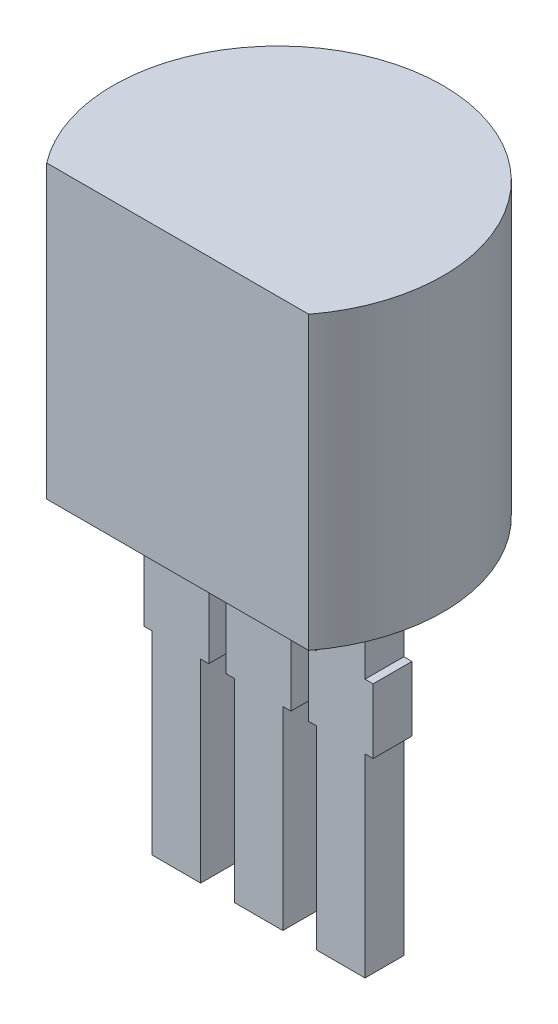
SolidWorks part; units mm, degrees
ref_plane "Спереди" through (0, 0, 0) normal (0, 0, 1) x (1, 0, 0)
ref_plane "Сверху" through (0, 0, 0) normal (0, 1, 0) x (1, 0, 0)
ref_plane "Справа" through (0, 0, 0) normal (1, 0, 0) x (0, 0, -1)
sketch "Эскиз1" plane through (0, 0, 0) normal (0, 1, 0) x (1, 0, 0)
  line L0 (-2.0248, -1.55) -> (2.0248, -1.55)
  arc A0 (2.0248, -1.55) -> (-2.0248, -1.55) centre (0, 0) ccw
  point P5 (0, 0)
  point P6 (2.0248, -1.55)
  point P7 (-2.0248, -1.55)
  dimension "D1" = 5.1
  dimension "D2" = 1.55
extrude "Бобышка-Вытянуть1" add sketch "Эскиз1" along normal blind 4.5
sketch "Эскиз3" plane through (0, 0, 0) normal (0, 0, 1) x (1, 0, 0)
  line L0 (0, 2.0104) -> (0, -3.7717) construction
  line L1 (-1.27, -4.7725) -> (-1.27, 1.9377) construction
  line L2 (1.27, -4.7725) -> (1.27, 1.8672) construction
  line L3 (-1.645, 0) -> (-1.645, -1.2)
  line L4 (-1.645, -1.2) -> (-1.77, -1.2)
  line L5 (-1.77, -1.2) -> (-1.77, -2.2)
  line L6 (-1.77, -2.2) -> (-1.645, -2.2)
  line L7 (-1.645, -2.2) -> (-1.645, -5.2)
  line L8 (-1.645, -5.2) -> (-0.895, -5.2)
  line L9 (-2.0248, 0) -> (2.0248, 0) construction
  line L10 (-0.895, -2.2) -> (-0.895, -5.2)
  line L11 (-0.77, -2.2) -> (-0.895, -2.2)
  line L12 (-0.77, -1.2) -> (-0.77, -2.2)
  line L13 (-0.895, -1.2) -> (-0.77, -1.2)
  line L14 (-0.895, 0) -> (-0.895, -1.2)
  line L15 (-0.5, -1.2) -> (-0.5, -2.2)
  line L16 (-0.375, 0) -> (-0.375, -1.2)
  line L17 (-0.375, -1.2) -> (-0.5, -1.2)
  line L18 (0.375, 0) -> (0.375, -1.2)
  line L19 (-0.375, -5.2) -> (0.375, -5.2)
  line L20 (0.375, -2.2) -> (0.375, -5.2)
  line L21 (-0.375, -2.2) -> (-0.375, -5.2)
  line L22 (0.5, -1.2) -> (0.5, -2.2)
  line L23 (-0.5, -2.2) -> (-0.375, -2.2)
  line L24 (0.5, -2.2) -> (0.375, -2.2)
  line L25 (0.895, -1.2) -> (0.77, -1.2)
  line L26 (0.77, -1.2) -> (0.77, -2.2)
  line L27 (0.77, -2.2) -> (0.895, -2.2)
  line L28 (0.895, -2.2) -> (0.895, -5.2)
  line L29 (1.645, -5.2) -> (0.895, -5.2)
  line L30 (1.645, -2.2) -> (1.645, -5.2)
  line L31 (1.77, -2.2) -> (1.645, -2.2)
  line L32 (1.77, -1.2) -> (1.77, -2.2)
  line L33 (1.645, -1.2) -> (1.77, -1.2)
  line L34 (1.645, 0) -> (1.645, -1.2)
  line L35 (0.895, 0) -> (0.895, -1.2)
  line L36 (0.5, -1.2) -> (0.375, -1.2)
  line L37 (-1.645, 0) -> (-0.895, 0)
  line L38 (-0.375, 0) -> (0.375, 0)
  line L39 (0.895, 0) -> (1.645, 0)
  point P18 (-1.27, -5.2)
  point P30 (0, -5.2)
  point P47 (0, 0)
  point P48 (0, 0)
  point P49 (0, 0)
  dimension "D1" = 1.27
  dimension "D2" = 1.2
  dimension "D3" = 1
  dimension "D4" = 0.375
  dimension "D5" = 0.5
  dimension "D6" = 3
extrude "Бобышка-Вытянуть2" add sketch "Эскиз3" along normal mid plane 0.6 contours L38 L16 L17 L15 L23 L21 L19 L20 L24 L22 L36 L18 | L39 L35 L25 L26 L27 L28 L29 L30 L31 L32 L33 L34 | L5 L6 L7 L8 L10 L11 L12 L13 L14 L37 L3 L4
